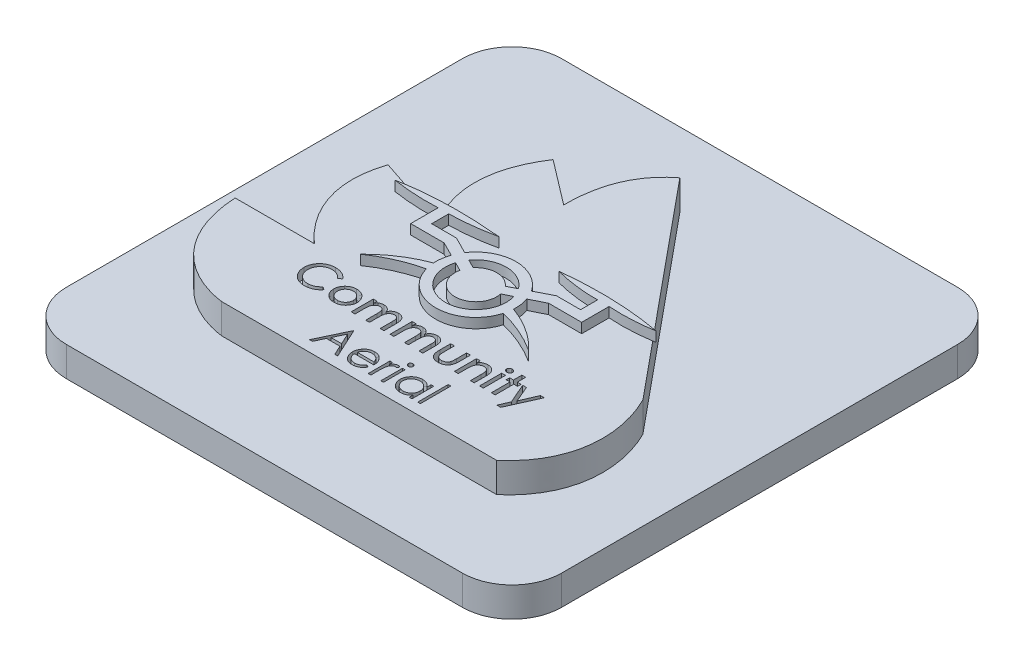
SolidWorks part; units mm, degrees
ref_plane "Alzado" through (0, 0, 0) normal (0, 0, 1) x (1, 0, 0)
ref_plane "Planta" through (0, 0, 0) normal (0, 1, 0) x (1, 0, 0)
ref_plane "Vista lateral" through (0, 0, 0) normal (1, 0, 0) x (0, 0, -1)
sketch "Croquis1" plane through (0, 0, 0) normal (0, 1, 0) x (1, 0, 0)
  line L1 (-20, -25) -> (20, -25)
  line L2 (-25, -20) -> (-25, 20)
  line L3 (-20, 25) -> (20, 25)
  line L4 (25, -20) -> (25, 20)
  arc A0 (-20, -25) -> (-25, -20) centre (-20, -20) cw
  arc A1 (20, -25) -> (25, -20) centre (20, -20) ccw
  arc A2 (20, 25) -> (25, 20) centre (20, 20) cw
  arc A3 (-25, 20) -> (-20, 25) centre (-20, 20) cw
  point P0 (0, 0)
  point P12 (25, 25)
  point P15 (-25, 25)
  dimension "D2" = 5
  dimension "D1" = 50
extrude "Saliente-Extruir1" add sketch "Croquis1" along normal blind 3
sketch "Croquis6" plane through (0, 3, 0) normal (0, 1, 0) x (1, 0, 0)
  line L0 (58.8044, -224.9095) -> (392.1377, -224.9095) construction
  line L1 (-0.5955, 17.5492) -> (16.9651, -3.747)
  line L2 (14.8644, -16.4104) -> (-12.9152, -16.4104)
  line L3 (-21.2898, -6.6689) -> (-13.2744, -6.6689)
  line L4 (-16.4707, 3.9527) -> (-8.8451, 1.4109)
  line L5 (-8.5911, 12.7403) -> (-4.0838, 9.3041)
  spline S0 degree 2 poles (-4.0838, 9.3041) (-4.1437, 14.8201) (-0.5955, 17.5492) knots 0 0 0 1 1 1
  spline S1 degree 3 poles (16.9651, -3.747) (18.8721, -7.5774) (19.1621, -12.7039) (14.8644, -16.4104) knots 0 0 0 0 1 1 1 1
  spline S2 degree 3 poles (-12.9152, -16.4104) (-17.1562, -15.8182) (-20.9541, -12.7124) (-21.2898, -6.6689) knots 0 0 0 0 1 1 1 1
  spline S3 degree 3 poles (-13.2744, -6.6689) (-16.066, -4.2446) (-17.9581, -0.5093) (-16.4707, 3.9527) knots 0 0 0 0 1 1 1 1
  spline S4 degree 3 poles (-8.8451, 1.4109) (-10.9647, 4.5376) (-11.3302, 8.5777) (-8.5911, 12.7403) knots 0 0 0 0 1 1 1 1
extrude "Saliente-Extruir2" add sketch "Croquis6" along normal blind 3
sketch "Croquis8" plane through (0, 6, 0) normal (0, 1, 0) x (1, 0, 0)
  line L0 (63.9954, 222.0712) -> (397.3288, 222.0712) construction
  line L1 (4.7524, -1.0474) -> (3.2767, -1.7774)
  line L2 (-5.802, -1.0474) -> (-4.3712, -1.7661)
  line L3 (-5.6011, 0) -> (-3.9195, -0.8588)
  line L4 (-3.3, 0) -> (3.3, 0) construction
  line L5 (4.4844, 0) -> (2.8187, -0.8552)
  line L6 (-8.115, 0) -> (-5.6011, 0)
  line L7 (-5.802, -1.0474) -> (-9.1837, -1.0474)
  line L8 (-9.1837, -1.0474) -> (-9.1837, 1.7215)
  line L9 (-8.115, 0) -> (-8.115, 1.7215)
  line L10 (4.7524, -1.0474) -> (8.082, -1.0474)
  line L11 (8.082, -1.0474) -> (8.082, 1.7215)
  line L12 (4.4844, 0) -> (6.923, 0)
  line L13 (6.923, 0) -> (6.923, 1.7215)
  line L14 (-3.4964, -2.2055) -> (-2.6105, -2.6505)
  line L15 (-3.0496, -1.303) -> (-2.1707, -1.7519)
  line L16 (1.9499, -1.3012) -> (1.0722, -1.7519)
  line L17 (2.3996, -2.2113) -> (1.5121, -2.6505)
  arc A0 (-2.6105, -2.6505) -> (1.5121, -2.6505) centre (-0.5492, -3.1025) ccw
  arc A1 (-4.3712, -1.7661) -> (-4.5914, -3.3355) centre (-0.5492, -3.1025) ccw
  arc A2 (-3.4964, -2.2055) -> (2.3996, -2.2113) centre (-0.5492, -3.1025) ccw
  arc A3 (1.0722, -1.7519) -> (-2.1707, -1.7519) centre (-0.5492, -3.1025) ccw
  arc A4 (1.9499, -1.3012) -> (-3.0496, -1.303) centre (-0.5492, -3.1025) ccw
  arc A5 (2.8187, -0.8552) -> (-3.9195, -0.8588) centre (-0.5492, -3.1025) ccw
  arc A6 (3.4929, -3.3355) -> (3.2767, -1.7774) centre (-0.5492, -3.1025) ccw
  arc A7 (-4.4409, -4.2198) -> (3.3424, -4.2198) centre (-0.5492, -3.1025) ccw
  spline S0 degree 2 poles (-4.4409, -4.2198) (-6.8974, -4.7764) (-9.0483, -6.2566) knots 0 0 0 1 1 1
  spline S1 degree 2 poles (-9.0483, -6.2566) (-7.0865, -4.2701) (-4.5914, -3.3355) knots 0 0 0 1 1 1
  spline S2 degree 2 poles (3.3424, -4.2198) (5.7358, -4.8129) (7.8663, -6.1831) knots 0 0 0 1 1 1
  spline S3 degree 2 poles (3.4929, -3.3355) (6.0863, -4.2752) (7.8663, -6.1831) knots 0 0 0 1 1 1
  spline S4 degree 2 poles (-9.1837, 1.7215) (-11.4185, 1.6022) (-13.7701, 1.958) knots 0 0 0 1 1 1
  spline S5 degree 3 poles (-13.7701, 1.958) (-10.3907, 2.6164) (-6.9709, 2.5659) (-3.5892, 2.2639) knots 0 0 0 0 1 1 1 1
  spline S6 degree 2 poles (-8.115, 1.7215) (-5.8159, 1.7783) (-3.5892, 2.2639) knots 0 0 0 1 1 1
  spline S7 degree 2 poles (6.923, 1.7215) (4.6896, 1.6896) (2.4888, 2.2639) knots 0 0 0 1 1 1
  spline S8 degree 2 poles (2.4888, 2.2639) (7.6243, 2.8585) (12.6028, 1.958) knots 0 0 0 1 1 1
  spline S9 degree 2 poles (12.6028, 1.958) (10.3728, 1.5703) (8.082, 1.7215) knots 0 0 0 1 1 1
extrude "Saliente-Extruir3" add sketch "Croquis8" along normal blind 1
sketch "Croquis9" plane through (0, 6, 0) normal (0, 1, 0) x (1, 0, 0)
  line L0 (-11.9723, -10.7657) -> (13.0394, -10.7657) construction
  line L1 (-11.9723, -15.3046) -> (13.0394, -15.3046) construction
  text T0 "<b>Community</b>" font "Century Gothic" height 3
  text T1 "Aerial" font "Century Gothic" height 3
extrude "Cortar-Extruir1" cut sketch "Croquis9" against normal blind 1
